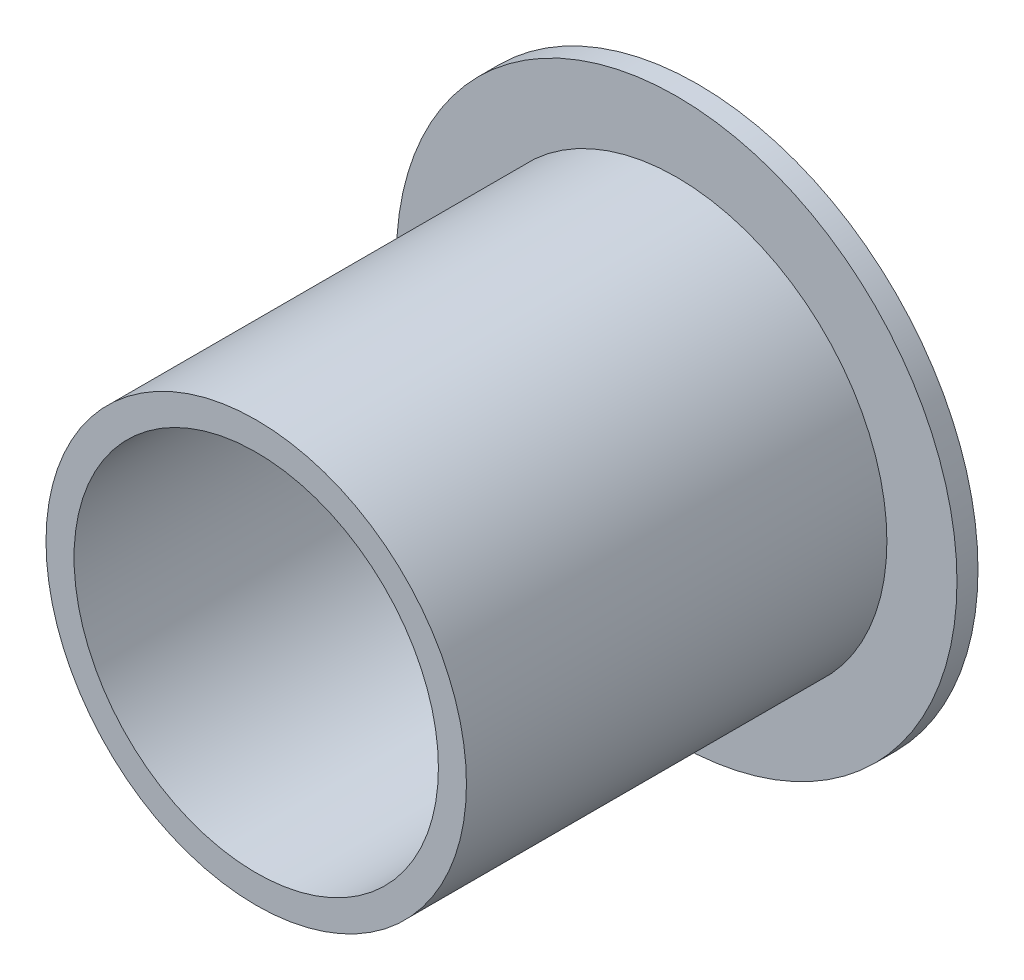
SolidWorks part; units mm, degrees
ref_plane "Front Plane" through (0, 0, 0) normal (0, 0, 1) x (1, 0, 0)
ref_plane "Top Plane" through (0, 0, 0) normal (0, 1, 0) x (1, 0, 0)
ref_plane "Right Plane" through (0, 0, 0) normal (1, 0, 0) x (0, 0, -1)
sketch "Sketch1" plane through (0, 0, 0) normal (0, 0, 1) x (1, 0, 0)
  circle A0 centre (0, 0) radius 20
  dimension "D1" = 40
extrude "Boss-Extrude1" add sketch "Sketch1" along normal blind 1.5
sketch "Sketch2" plane through (0, 0, 1.5) normal (0, 0, 1) x (1, 0, 0)
  circle A0 centre (0, 0) radius 15
  circle A1 centre (0, 0) radius 13
  dimension "D1" = 30
  dimension "D2" = 26
extrude "Boss-Extrude2" add sketch "Sketch2" along normal blind 30
sketch "Sketch3" plane through (0, 0, 0) normal (0, 0, -1) x (-1, 0, 0)
  circle A0 centre (0, 0) radius 10
  dimension "D1" = 20
extrude "Cut-Extrude1" cut sketch "Sketch3" against normal blind 30
